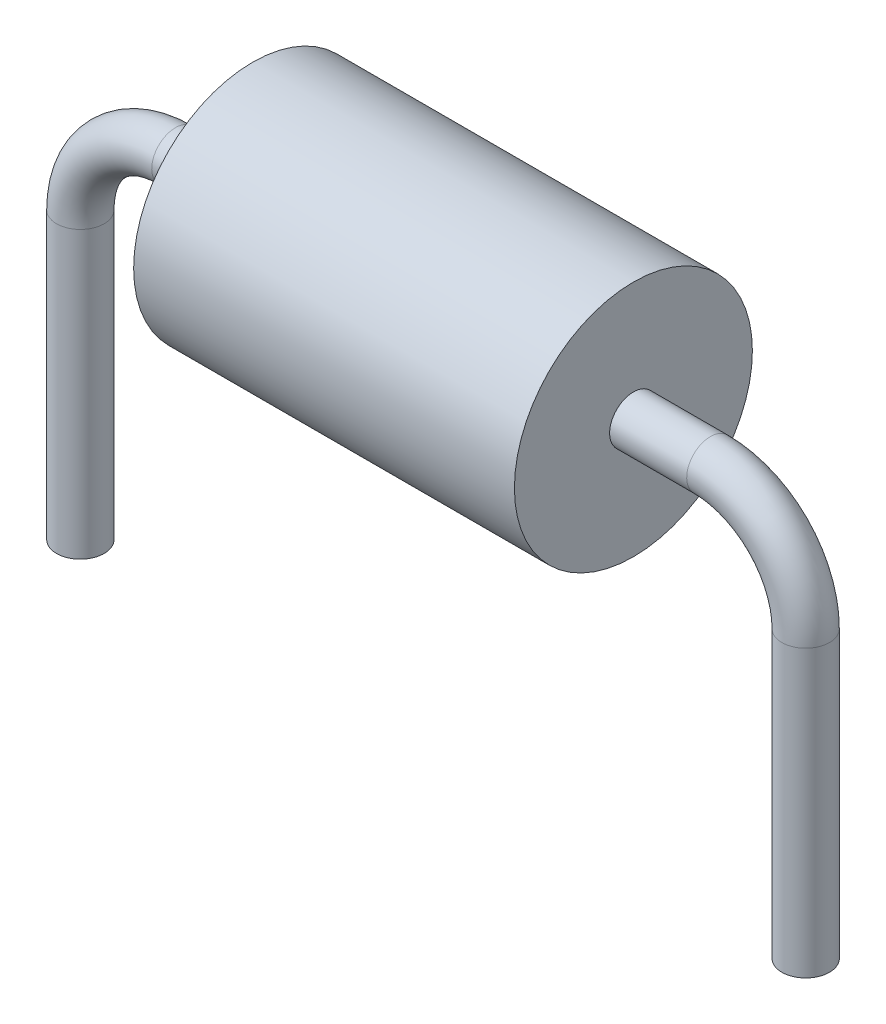
SolidWorks part; units mm, degrees
ref_plane "Front Plane" through (0, 0, 0) normal (0, 0, 1) x (1, 0, 0)
ref_plane "Top Plane" through (0, 0, 0) normal (0, 1, 0) x (1, 0, 0)
ref_plane "Right Plane" through (0, 0, 0) normal (1, 0, 0) x (0, 0, -1)
sketch "Sketch1" plane through (0, 0, 0) normal (0, 0, 1) x (1, 0, 0)
  line L0 (0, 0) -> (2.81, 0)
  line L1 (3.81, -1) -> (3.81, -4)
  line L2 (2.81, -1) -> (2.81, 0) construction
  line L3 (2.81, -1) -> (3.81, -1) construction
  arc A0 (2.81, 0) -> (3.81, -1) centre (2.81, -1) cw
  dimension "D2" = 1
  dimension "D1" = 3.81
  dimension "D3" = 4
sketch "Sketch2" plane through (0, 0, 0) normal (0, 0, 1) x (1, 0, 0)
  line L1 (0, 0) -> (2, 0)
  line L2 (0, 0) -> (0, -1.25)
  line L3 (0, -1.25) -> (2, -1.25)
  line L4 (2, 0) -> (2, -1.25)
  dimension "D1" = 2
  dimension "D2" = 1.25
revolve "Revolve1" add sketch "Sketch2" angle 360 about L0
sketch "Sketch3" plane through (2, 0, 0) normal (1, 0, 0) x (0, 0, -1)
  circle A0 centre (0, 0) radius 0.25
  dimension "D1" = 0.5
sweep "Sweep1" add profiles "Sketch3" path "Sketch1"
mirror "Mirror1" about plane through (0, 0, 0) normal (-1, 0, 0) of "Sweep1", "Revolve1"
